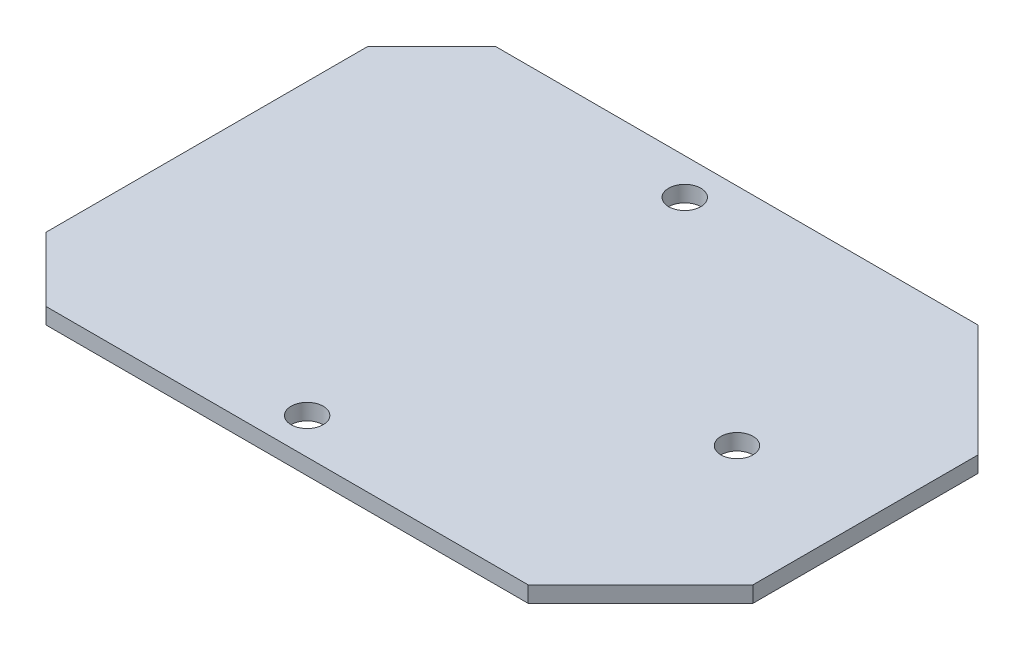
SolidWorks part; units mm, degrees
ref_plane "Front Plane" through (0, 0, 0) normal (0, 0, 1) x (1, 0, 0)
ref_plane "Top Plane" through (0, 0, 0) normal (0, 1, 0) x (1, 0, 0)
ref_plane "Right Plane" through (0, 0, 0) normal (1, 0, 0) x (0, 0, -1)
sketch "Sketch1" plane through (0, 0, 0) normal (0, 1, 0) x (1, 0, 0)
  line L0 (-13.587, -102.6838) -> (-13.587, -82.6838)
  line L1 (-13.587, -82.6838) -> (-9.587, -78.6838)
  line L2 (-9.587, -78.6838) -> (20.413, -78.6838)
  line L3 (20.413, -78.6838) -> (27.413, -85.6838)
  line L4 (27.413, -85.6838) -> (27.413, -99.6838)
  line L5 (27.413, -99.6838) -> (20.413, -106.6838)
  line L6 (20.413, -106.6838) -> (-9.587, -106.6838)
  line L7 (-9.587, -106.6838) -> (-13.587, -102.6838)
  point P2 (-14.4778, -102.8332)
  dimension "D1" = 28
  dimension "D2" = 7
  dimension "D3" = 7
  dimension "D4" = 4
  dimension "D5" = 4
  dimension "D6" = 135
  dimension "D7" = 30
extrude "Boss-Extrude1" add sketch "Sketch1" along normal blind 1
sketch "Sketch2" plane through (0, 1, 0) normal (0, 1, 0) x (1, 0, 0)
  line L0 (27.413, -99.6838) -> (27.413, -85.6838) construction
  line L1 (-9.587, -106.6838) -> (20.413, -106.6838) construction
  circle A0 centre (19.413, -92.6838) radius 1
  dimension "D1" = 2
  dimension "D2" = 8
  dimension "D3" = 14
extrude "Cut-Extrude1" cut sketch "Sketch2" against normal blind 1
sketch "Sketch4" plane through (0, 1, 0) normal (0, 1, 0) x (1, 0, 0)
  circle A0 centre (4.413, -104.4338) radius 1
  circle A1 centre (4.413, -80.9338) radius 1
  dimension "D1" = 2
  dimension "D2" = 2
extrude "Cut-Extrude2" cut sketch "Sketch4" against normal blind 1
